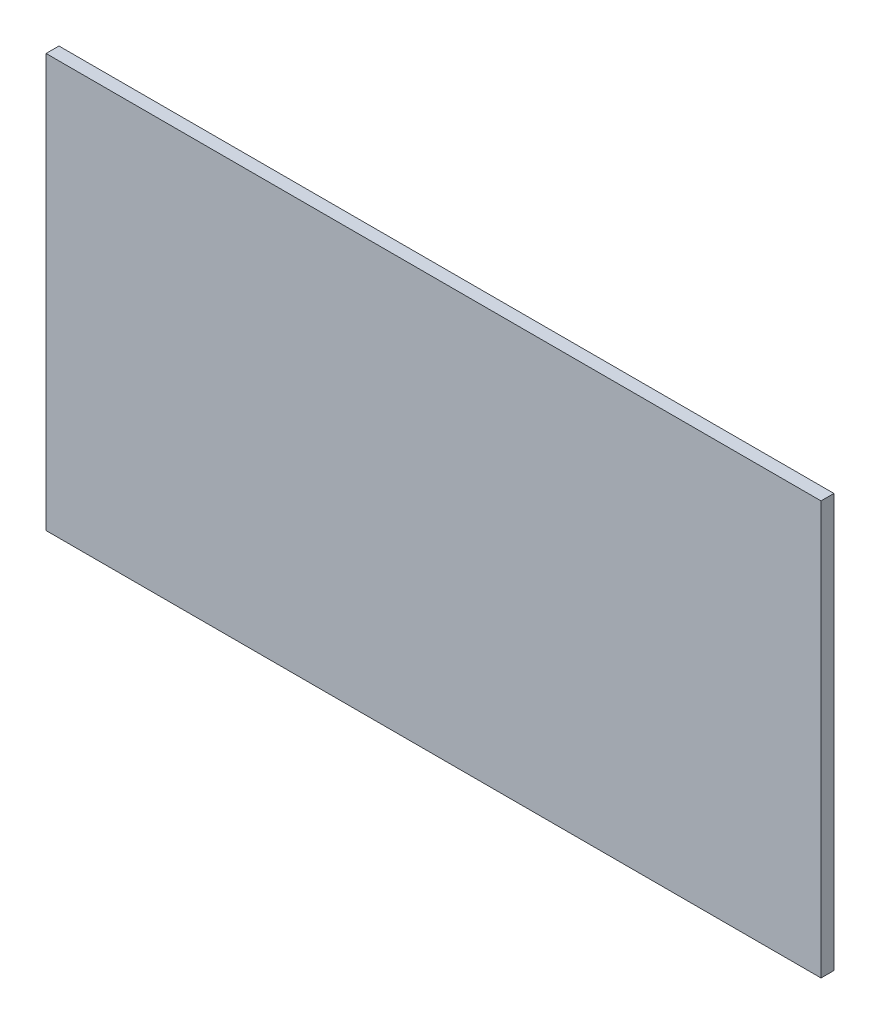
SolidWorks part; units mm, degrees
ref_plane "Front Plane" through (0, 0, 0) normal (0, 0, 1) x (1, 0, 0)
ref_plane "Top Plane" through (0, 0, 0) normal (0, 1, 0) x (1, 0, 0)
ref_plane "Right Plane" through (0, 0, 0) normal (1, 0, 0) x (0, 0, -1)
sketch "Sketch1" plane through (0, 0, 0) normal (0, 0, 1) x (1, 0, 0)
  line L1 (0, 0) -> (150.05, 0)
  line L2 (0, 0) -> (0, 80)
  line L3 (0, 80) -> (150.05, 80)
  line L4 (150.05, 0) -> (150.05, 80)
  dimension "D1" = 150.05
  dimension "D2" = 80
extrude "Boss-Extrude1" add sketch "Sketch1" along normal blind 2.5
sketch "Sketch2" plane through (0, 0, 0) normal (0, 0, -1) x (-1, 0, 0)
  line L0 (0, 0) -> (-150.05, 0) construction
  line L1 (-60.025, 11.7265) -> (-90.025, 11.7265)
  line L2 (-60.025, 11.7265) -> (-60.025, 16.7265)
  line L3 (-60.025, 16.7265) -> (-90.025, 16.7265)
  line L4 (-90.025, 11.7265) -> (-90.025, 16.7265)
  point P4 (-75.025, 11.7265)
  point P5 (-75.025, 0)
  point P6 (-75.025, 0)
  point P9 (0, 0)
  dimension "D1" = 5
  dimension "D2" = 30
extrude "Boss-Extrude2" add sketch "Sketch2" along normal blind 5
